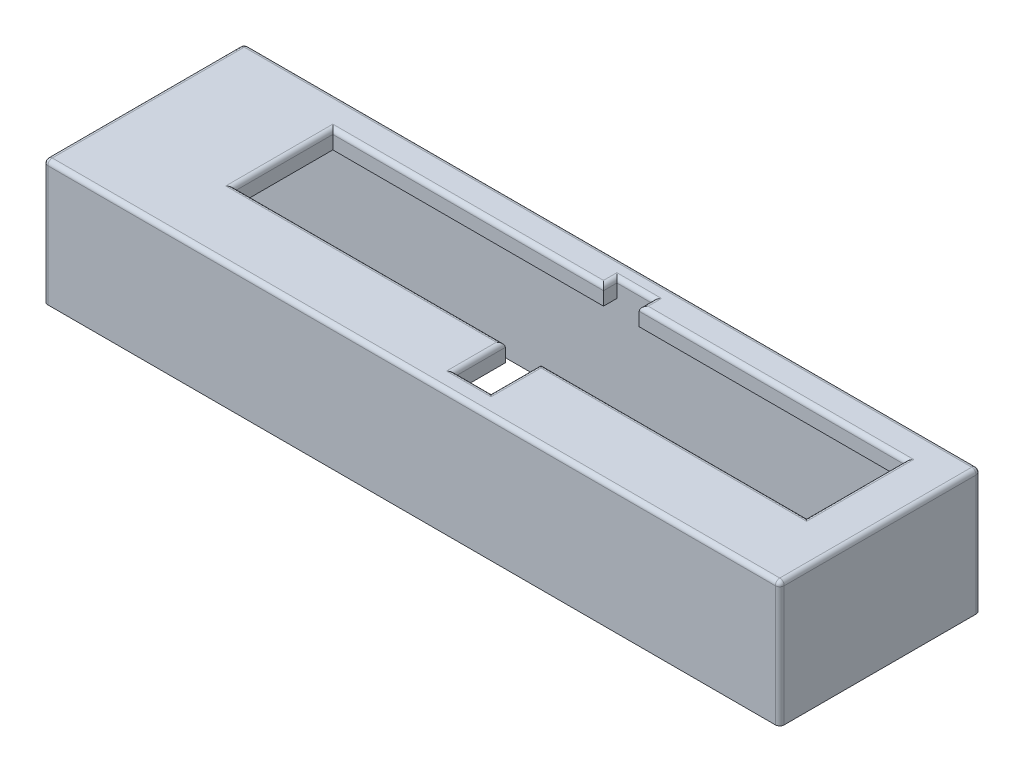
SolidWorks part; units mm, degrees
ref_plane "Front" through (0, 0, 0) normal (0, 0, 1) x (1, 0, 0)
ref_plane "Top" through (0, 0, 0) normal (0, 1, 0) x (1, 0, 0)
ref_plane "Right" through (0, 0, 0) normal (1, 0, 0) x (0, 0, -1)
sketch "Sketch1" plane through (0, 0, 0) normal (0, 1, 0) x (1, 0, 0)
  line L1 (-104.775, 22.86) -> (104.775, 22.86)
  line L2 (-104.775, 22.86) -> (-104.775, -34.29)
  line L3 (-104.775, -34.29) -> (104.775, -34.29)
  line L4 (104.775, 22.86) -> (104.775, -34.29)
  line L7 (-55, 0) -> (55, 0) construction
  point P0 (0, 0)
  dimension "D1" = 209.55
  dimension "D2" = 22.86
  dimension "D3" = 34.29
extrude "Boss-Extrude1" add sketch "Sketch1" along normal blind 5.08
sketch "Sketch2" plane through (0, 0, 0) normal (0, -1, 0) x (1, 0, 0)
  line L1 (-99.695, 29.21) -> (99.695, 29.21)
  line L2 (-99.695, 29.21) -> (-99.695, -17.78)
  line L3 (-99.695, -17.78) -> (99.695, -17.78)
  line L4 (99.695, 29.21) -> (99.695, -17.78)
  line L10 (104.775, -22.86) -> (104.775, 34.29)
  line L11 (104.775, 34.29) -> (-104.775, 34.29)
  line L12 (-104.775, 34.29) -> (-104.775, -22.86)
  line L13 (-104.775, -22.86) -> (104.775, -22.86)
  line L14 (104.775, -22.86) -> (104.775, 34.29)
  line L15 (104.775, 34.29) -> (-104.775, 34.29)
  line L16 (-104.775, 34.29) -> (-104.775, -22.86)
  line L17 (-104.775, -22.86) -> (104.775, -22.86)
  point P0 (0, 0)
  dimension "D2" = 5.08
  dimension "D3" = 5.08
  dimension "D4" = 5.08
  dimension "D1" = 0
extrude "Boss-Extrude2" add sketch "Sketch2" along normal blind 30.48 contours L14 L15 L16 L17 | L2 L1 L4 L3
sketch "Sketch3" plane through (0, 5.08, 0) normal (0, 1, 0) x (1, 0, 0)
  line L0 (104.775, 22.86) -> (-104.775, 22.86) construction
  line L1 (-92.0869, 13.97) -> (92.0869, 13.97)
  line L2 (-92.0869, 13.97) -> (-92.0869, -13.97)
  line L3 (-92.0869, -13.97) -> (92.0869, -13.97)
  line L4 (92.0869, 13.97) -> (92.0869, -13.97)
  line L5 (-92.0869, 13.97) -> (92.0869, -13.97) construction
  line L6 (-92.0869, -13.97) -> (92.0869, 13.97) construction
  line L7 (-70.6685, 13.97) -> (-70.6685, -13.97)
  line L13 (6.35, -13.97) -> (16.51, -13.97)
  line L18 (0, -19.558) -> (0, 19.558) construction
  line L19 (6.35, 13.97) -> (16.51, 13.97)
  line L20 (6.35, 13.97) -> (6.35, 17.78)
  line L21 (6.35, 17.78) -> (16.51, 17.78)
  line L22 (16.51, 13.97) -> (16.51, 17.78)
  line L28 (6.35, -13.97) -> (6.35, -28.179)
  line L29 (6.35, -28.179) -> (16.51, -28.179)
  line L30 (16.51, -13.97) -> (16.51, -28.179)
  point P0 (0, 0)
  dimension "D1" = 8.89
  dimension "D2" = 10.16
  dimension "D3" = 3.81
  dimension "D4" = 6.35
extrude "Cut-Extrude2" cut sketch "Sketch3" against normal up to next contours L1 L7 L3 L4
fillet "Fillet1" radius 1.27 20 edges at (0, 5.08, 34.29) (-104.775, 5.08, 5.715) (0, 5.08, -22.86) (104.775, 5.08, 5.715) (11.43, 5.08, 28.179) (16.51, 5.08, 21.0745) (54.2985, 5.08, 13.97) (92.0869, 5.08, 0) (54.2985, 5.08, -13.97) (16.51, 5.08, -15.875) (11.43, 5.08, -17.78) (6.35, 5.08, -15.875) (-32.1593, 5.08, -13.97) (-70.6685, 5.08, 0) (-32.1593, 5.08, 13.97) (6.35, 5.08, 21.0745) (104.775, -12.7, 34.29) (104.775, -12.7, -22.86) (-104.775, -12.7, 34.29) (-104.775, -12.7, -22.86)
